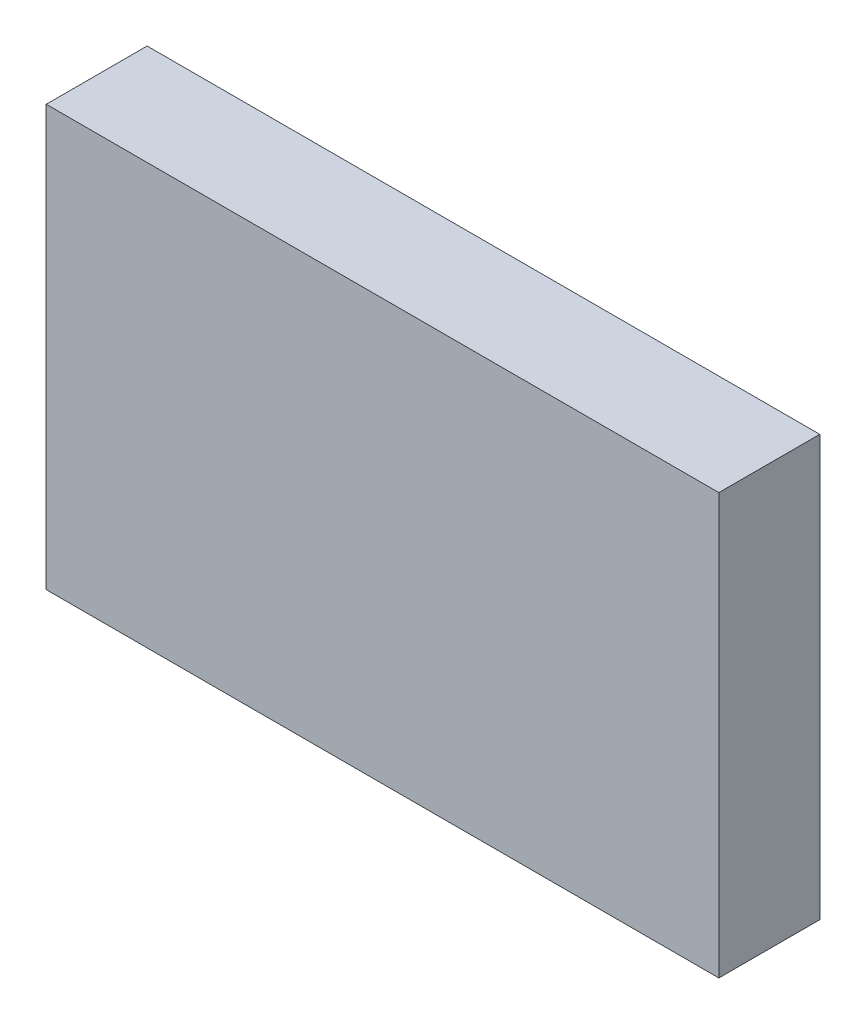
SolidWorks part; units mm, degrees
ref_plane "前视基准面" through (0, 0, 0) normal (0, 0, 1) x (1, 0, 0)
ref_plane "上视基准面" through (0, 0, 0) normal (0, 1, 0) x (1, 0, 0)
ref_plane "右视基准面" through (0, 0, 0) normal (1, 0, 0) x (0, 0, -1)
other "Configuration Table"
sketch "草图1" plane through (0, 0, 0) normal (0, 0, 1) x (1, 0, 0)
  line L1 (0, 0) -> (80, 0)
  line L2 (0, 0) -> (0, 50)
  line L3 (0, 50) -> (80, 50)
  line L4 (80, 0) -> (80, 50)
extrude "凸台-拉伸1" add sketch "草图1" along normal blind 12
other "分型线1"
